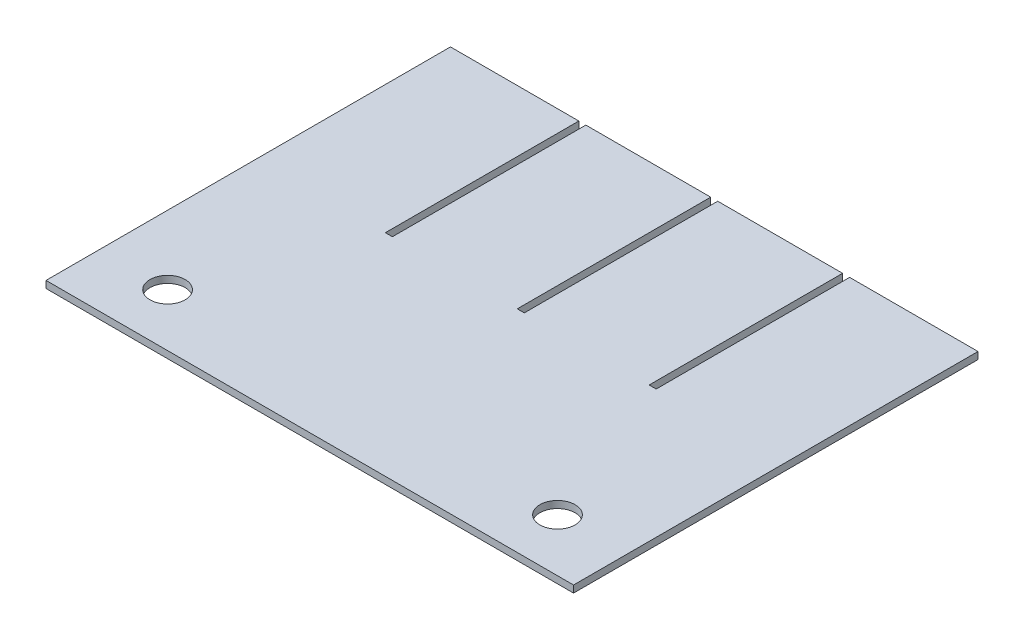
SolidWorks part; units mm, degrees
ref_plane "Front Plane" through (0, 0, 0) normal (0, 0, 1) x (1, 0, 0)
ref_plane "Top Plane" through (0, 0, 0) normal (0, 1, 0) x (1, 0, 0)
ref_plane "Right Plane" through (0, 0, 0) normal (1, 0, 0) x (0, 0, -1)
sketch "Sketch1" plane through (0, 0, 0) normal (0, 1, 0) x (1, 0, 0)
  line L0 (1, 57.5) -> (36.5, 57.5)
  line L1 (-75, 57.5) -> (-38.5, 57.5)
  line L2 (-75, 57.5) -> (-75, -57.5)
  line L3 (-75, -57.5) -> (75, -57.5)
  line L4 (75, 57.5) -> (75, -57.5)
  line L5 (-75, 57.5) -> (75, -57.5) construction
  line L6 (-75, -57.5) -> (75, 57.5) construction
  line L8 (-1, 57.5) -> (-1, 2.5)
  line L9 (-1, 2.5) -> (1, 2.5)
  line L10 (1, 57.5) -> (1, 2.5)
  line L11 (0, -7.6087) -> (0, 12.3363) construction
  line L13 (-38.5, 57.5) -> (-38.5, 2.5)
  line L14 (-38.5, 2.5) -> (-36.5, 2.5)
  line L15 (-36.5, 57.5) -> (-36.5, 2.5)
  line L16 (38.5, 2.5) -> (36.5, 2.5)
  line L17 (36.5, 57.5) -> (36.5, 2.5)
  line L19 (38.5, 57.5) -> (38.5, 2.5)
  line L20 (-36.5, 57.5) -> (-1, 57.5)
  line L21 (38.5, 57.5) -> (75, 57.5)
  circle A0 centre (-55.4348, -42.5) radius 5
  circle A1 centre (55.4348, -42.5) radius 5
  point P0 (0, 0)
  dimension "D9" = 10
  dimension "D10" = 10
  dimension "D1" = 150
  dimension "D2" = 115
  dimension "D3" = 2
  dimension "D4" = 55
  dimension "D5" = 74
  dimension "D6" = 55
  dimension "D7" = 2
  dimension "D8" = 36.5
  dimension "D11" = 15
  dimension "D12" = 15
extrude "Boss-Extrude1" add sketch "Sketch1" along normal blind 2
